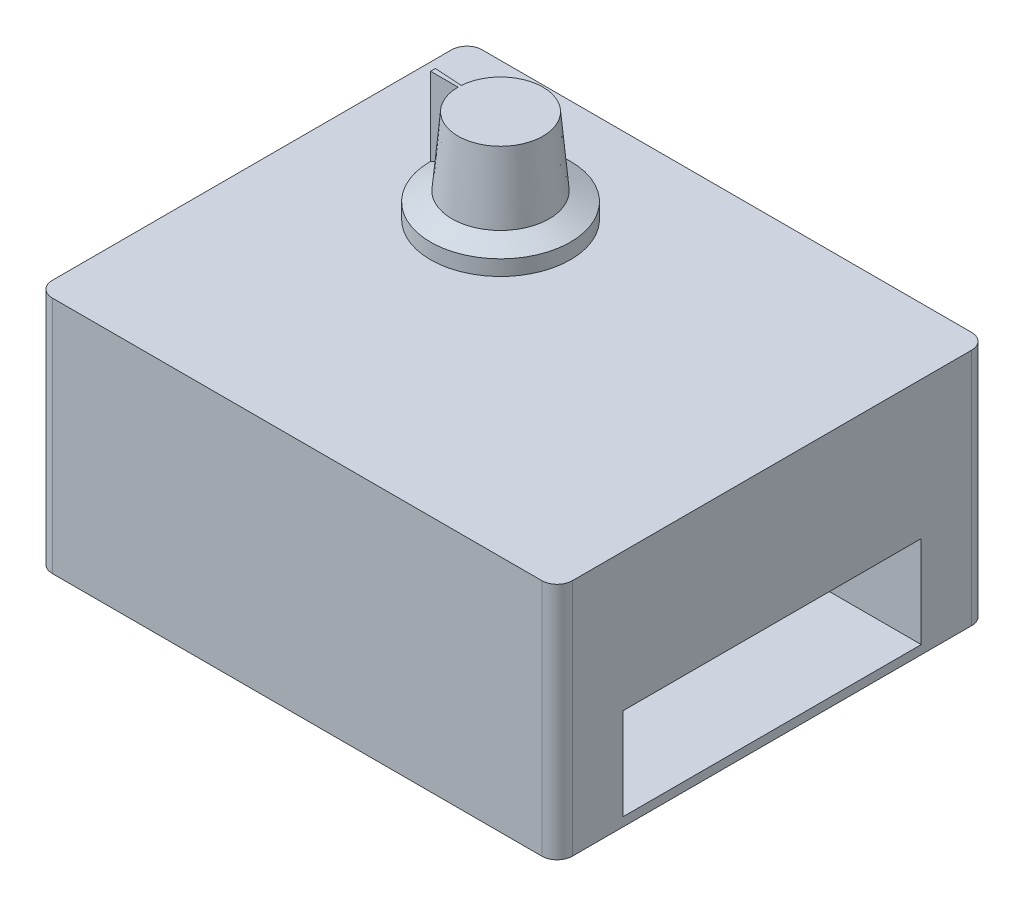
SolidWorks part; units mm, degrees
ref_plane "Front Plane" through (0, 0, 0) normal (0, 0, 1) x (1, 0, 0)
ref_plane "Top Plane" through (0, 0, 0) normal (0, 1, 0) x (1, 0, 0)
ref_plane "Right Plane" through (0, 0, 0) normal (1, 0, 0) x (0, 0, -1)
sketch "Sketch1" plane through (0, 0, 0) normal (0, 1, 0) x (1, 0, 0)
  line L1 (0, 0) -> (86.36, 0)
  line L2 (0, 0) -> (0, -71.374)
  line L3 (0, -71.374) -> (86.36, -71.374)
  line L4 (86.36, 0) -> (86.36, -71.374)
  dimension "D1" = 71.374
  dimension "D2" = 86.36
extrude "Boss-Extrude1" add sketch "Sketch1" along normal blind 39.624
fillet "Fillet1" radius 2.54 4 edges at (0, 19.812, 0) (86.36, 19.812, 0) (86.36, 19.812, 71.374) (0, 19.812, 71.374)
sketch "Sketch2" plane through (0, 0, 0) normal (-1, 0, 0) x (0, 0, 1)
  line L0 (35.687, 39.624) -> (35.687, 0) construction
  line L1 (30.226, 33.02) -> (30.48, 33.02)
  line L2 (28.448, 31.242) -> (28.448, 24.892)
  line L3 (30.226, 23.114) -> (30.48, 23.114)
  line L4 (32.258, 31.242) -> (32.258, 24.892)
  line L5 (2.54, 39.624) -> (68.834, 39.624) construction
  line L6 (2.54, 0) -> (68.834, 0) construction
  line L7 (0, 0) -> (0, 39.624) construction
  line L8 (41.148, 23.114) -> (40.894, 23.114)
  line L9 (42.926, 31.242) -> (42.926, 24.892)
  line L10 (39.116, 31.242) -> (39.116, 24.892)
  line L11 (41.148, 33.02) -> (40.894, 33.02)
  arc A0 (28.448, 24.892) -> (30.226, 23.114) centre (30.226, 24.892) ccw
  arc A1 (30.48, 23.114) -> (32.258, 24.892) centre (30.48, 24.892) ccw
  arc A2 (30.226, 33.02) -> (28.448, 31.242) centre (30.226, 31.242) ccw
  arc A3 (30.48, 33.02) -> (32.258, 31.242) centre (30.48, 31.242) cw
  arc A4 (40.894, 23.114) -> (39.116, 24.892) centre (40.894, 24.892) cw
  arc A5 (42.926, 24.892) -> (41.148, 23.114) centre (41.148, 24.892) cw
  arc A6 (40.894, 33.02) -> (39.116, 31.242) centre (40.894, 31.242) ccw
  arc A7 (41.148, 33.02) -> (42.926, 31.242) centre (41.148, 31.242) cw
  point P14 (28.448, 23.114)
  point P19 (28.448, 33.02)
  point P22 (32.258, 33.02)
  dimension "D5" = 1.778
  dimension "D1" = 3.81
  dimension "D2" = 9.906
  dimension "D3" = 28.448
  dimension "D4" = 23.114
extrude "Cut-Extrude1" cut sketch "Sketch2" against normal blind 25.4
fillet "Fillet2" radius 1.27 16 edges at (0, 28.067, 42.926) (0, 23.6348, 42.4052) (0, 23.114, 41.021) (0, 23.6348, 39.6368) (0, 28.067, 39.116) (0, 32.4992, 39.6368) (0, 33.02, 41.021) (0, 33.02, 30.353) (0, 32.4992, 31.7372) (0, 28.067, 32.258) (0, 23.6348, 31.7372) (0, 23.114, 30.353) (0, 23.6348, 28.9688) (0, 28.067, 28.448) (0, 32.4992, 42.4052) (0, 32.4992, 28.9688)
sketch "Sketch4" plane through (86.36, 0, 0) normal (1, 0, 0) x (0, 0, -1)
  line L1 (-60.452, 1.4732) -> (-10.922, 1.4732)
  line L2 (-60.452, 1.4732) -> (-60.452, 16.7132)
  line L3 (-60.452, 16.7132) -> (-10.922, 16.7132)
  line L4 (-10.922, 1.4732) -> (-10.922, 16.7132)
  line L5 (-71.374, 0) -> (-71.374, 39.624) construction
  line L6 (0, 39.624) -> (0, 0) construction
  line L7 (-68.834, 0) -> (-2.54, 0) construction
  dimension "D1" = 15.24
  dimension "D2" = 10.922
  dimension "D3" = 10.922
  dimension "D4" = 1.4732
extrude "Cut-Extrude2" cut sketch "Sketch4" against normal blind 50.8
sketch "Sketch5" plane through (0, 39.624, 0) normal (0, 1, 0) x (1, 0, 0)
  line L0 (28.448, -71.374) -> (28.448, 0) construction
  line L1 (2.54, -71.374) -> (83.82, -71.374) construction
  line L2 (83.82, 0) -> (2.54, 0) construction
  line L3 (86.36, -22.86) -> (0, -22.86) construction
  line L4 (86.36, -68.834) -> (86.36, -2.54) construction
  line L5 (0, -2.54) -> (0, -68.834) construction
  circle A0 centre (28.448, -22.86) radius 11.6205
  point P12 (28.448, -22.86)
  dimension "D3" = 23.241
  dimension "D1" = 28.448
  dimension "D2" = 22.86
extrude "Boss-Extrude2" add sketch "Sketch5" along normal blind 15.494
sketch "Sketch6" plane through (0, 55.118, 0) normal (0, 1, 0) x (1, 0, 0)
  line L0 (40.0685, -22.86) -> (16.8275, -22.86) construction
  line L1 (28.448, -34.4805) -> (28.448, -11.2395) construction
  circle A0 centre (28.448, -22.86) radius 11.6205 construction
  point P8 (28.448, -22.86)
ref_plane "Plane1" through (0, 0, 22.86) normal (0, 0, -1) x (-1, 0, 0)
ref_axis "Axis1" through (28.448, 55.118, 22.86) along (0, 1, 0)
sketch "Sketch7" plane through (0, 0, 22.86) normal (0, 0, -1) x (-1, 0, 0)
  line L0 (-16.8275, 39.624) -> (-16.8275, 55.118) construction
  line L1 (-16.8275, 42.164) -> (-20.3835, 43.7272)
  line L2 (-20.3835, 43.7272) -> (-21.3995, 55.118)
  line L3 (-40.0685, 55.118) -> (-16.8275, 55.118) construction
  line L4 (-21.3995, 55.118) -> (-16.8275, 55.118)
  line L5 (-16.8275, 55.118) -> (-16.8275, 42.164)
  point P0 (-16.8275, 42.164)
  point P6 (-20.3835, 43.7272)
  dimension "D1" = 2.54
  dimension "D2" = 4.572
  dimension "D3" = 3.556
  dimension "D4" = 11.3908
revolve "Cut-Revolve1" cut sketch "Sketch7" angle 356 about axis through (28.448, 55.118, 22.86) along (0, 1, 0)
